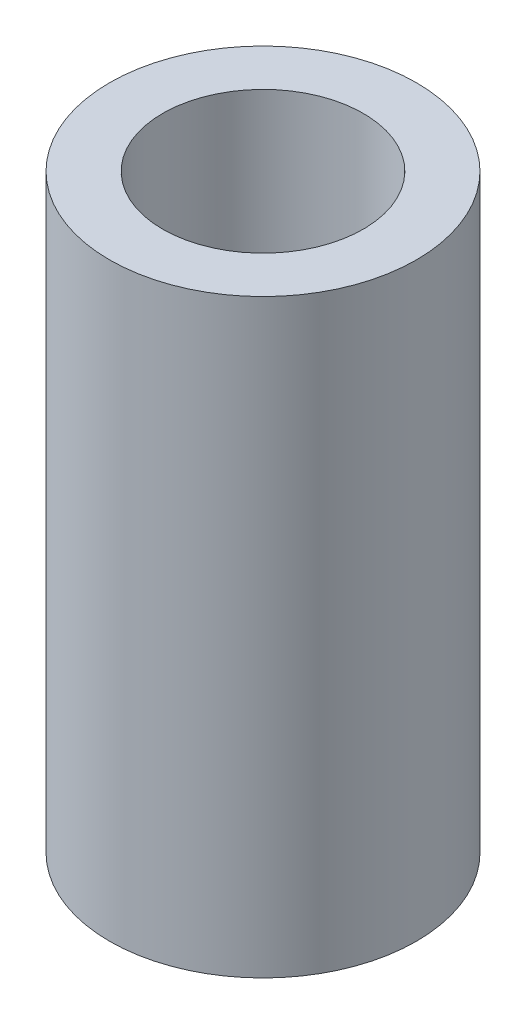
SolidWorks part; units mm, degrees
material "1060 Сплав"
ref_plane "Спереди" through (0, 0, 0) normal (0, 0, 1) x (1, 0, 0)
ref_plane "Сверху" through (0, 0, 0) normal (0, 1, 0) x (1, 0, 0)
ref_plane "Справа" through (0, 0, 0) normal (1, 0, 0) x (0, 0, -1)
sketch "Эскиз1" plane through (0, 0, 0) normal (0, 1, 0) x (1, 0, 0)
  circle A0 centre (0, 0) radius 6.5
  circle A1 centre (0, 0) radius 4.25
  dimension "D1" = 8.5
  dimension "D2" = 13
extrude "Бобышка-Вытянуть1" add sketch "Эскиз1" along normal blind 25
